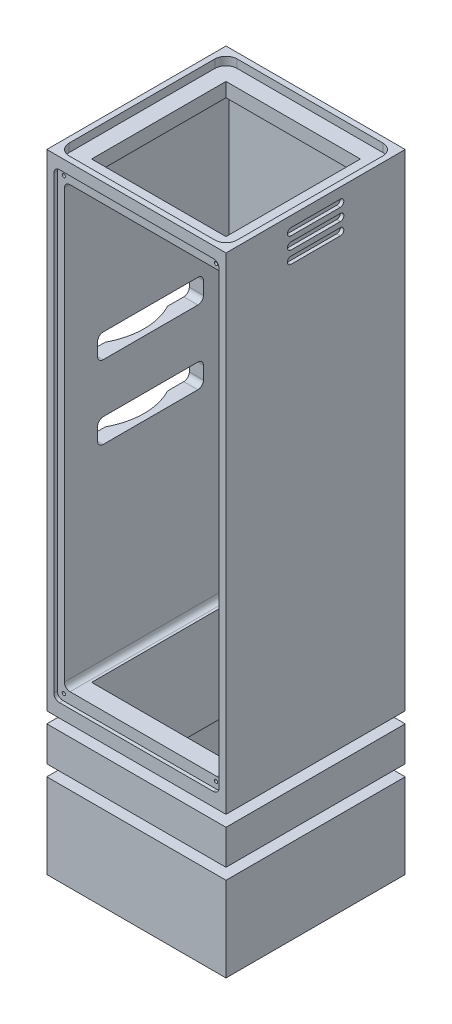
SolidWorks part; units mm, degrees
ref_plane "Front Plane" through (0, 0, 0) normal (0, 0, 1) x (1, 0, 0)
ref_plane "Top Plane" through (0, 0, 0) normal (0, 1, 0) x (1, 0, 0)
ref_plane "Right Plane" through (0, 0, 0) normal (1, 0, 0) x (0, 0, -1)
sketch "Sketch1" plane through (0, 0, 0) normal (0, 1, 0) x (1, 0, 0)
  line L0 (6.35, 44.45) -> (44.45, 44.45)
  line L1 (0, 0) -> (50.8, 0)
  line L2 (0, 0) -> (0, 50.8)
  line L3 (0, 50.8) -> (50.8, 50.8)
  line L4 (50.8, 0) -> (50.8, 50.8)
  line L5 (44.45, 6.35) -> (44.45, 44.45)
  line L6 (6.35, 6.35) -> (44.45, 6.35)
  line L7 (6.35, 6.35) -> (6.35, 44.45)
  dimension "D1" = 50.8
  dimension "D2" = 6.35
extrude "Boss-Extrude1" add sketch "Sketch1" along normal blind 178
sketch "Sketch2" plane through (0, 0, 0) normal (0, -1, 0) x (1, 0, 0)
  line L0 (47.8, -3) -> (3, -3)
  line L1 (3, -3) -> (3, -47.8)
  line L2 (3, -47.8) -> (47.8, -47.8)
  line L3 (47.8, -47.8) -> (47.8, -3)
  line L4 (6.35, -44.45) -> (44.45, -44.45)
  line L5 (6.35, -6.35) -> (6.35, -44.45)
  line L6 (44.45, -6.35) -> (6.35, -6.35)
  line L7 (44.45, -44.45) -> (44.45, -6.35)
  line L8 (6.35, -44.45) -> (44.45, -44.45)
  line L9 (6.35, -6.35) -> (6.35, -44.45)
  line L10 (44.45, -6.35) -> (6.35, -6.35)
  line L11 (44.45, -44.45) -> (44.45, -6.35)
  line L12 (0, -50.8) -> (0, 0) construction
  dimension "D2" = 3
  dimension "D1" = 0
extrude "Cut-Extrude1" cut sketch "Sketch2" against normal blind 20
sketch "Sketch3" plane through (0, 0, 0) normal (0, 0, 1) x (1, 0, 0)
  line L0 (0, 0) -> (50.8, 0) construction
  line L1 (2, 171.65) -> (48.8, 171.65)
  line L2 (2, 171.65) -> (2, 47.175)
  line L3 (2, 47.175) -> (48.8, 47.175)
  line L4 (48.8, 171.65) -> (48.8, 47.175)
  line L5 (0, 178) -> (0, 0) construction
  line L6 (50.8, 178) -> (50.8, 0) construction
  line L7 (0, 178) -> (50.8, 178) construction
  dimension "D1" = 47.175
  dimension "D2" = 2
  dimension "D3" = 2
  dimension "D4" = 6.35
extrude "Cut-Extrude2" cut sketch "Sketch3" against normal blind 47.625
sketch "Sketch4" plane through (0, 0, 0) normal (0, 0, 1) x (1, 0, 0)
  line L0 (0, 178) -> (0, 0) construction
  line L1 (0, 27.175) -> (50.8, 27.175)
  line L2 (0, 27.175) -> (0, 24)
  line L3 (0, 24) -> (50.8, 24)
  line L4 (50.8, 27.175) -> (50.8, 24)
  line L5 (50.8, 178) -> (50.8, 0) construction
  line L6 (0, 0) -> (50.8, 0) construction
  line L8 (0, 37) -> (50.8, 37)
  line L9 (0, 37) -> (0, 40.175)
  line L10 (0, 40.175) -> (50.8, 40.175)
  line L11 (50.8, 37) -> (50.8, 40.175)
  dimension "D1" = 24
  dimension "D2" = 3.175
  dimension "D3" = 13
extrude "Cut-Extrude3" cut sketch "Sketch4" against normal blind 3.175
sketch "Sketch5" plane through (0, 0, 0) normal (0, 0, 1) x (1, 0, 0)
  line L0 (50.8, 40.175) -> (0, 40.175) construction
  line L1 (0, 37) -> (3.175, 37)
  line L2 (0, 37) -> (0, 40.175)
  line L3 (0, 40.175) -> (3.175, 40.175)
  line L4 (3.175, 37) -> (3.175, 40.175)
  line L5 (0, 24) -> (50.8, 24) construction
  line L6 (0, 27.175) -> (3.175, 27.175)
  line L7 (0, 27.175) -> (0, 24)
  line L8 (0, 24) -> (3.175, 24)
  line L9 (3.175, 27.175) -> (3.175, 24)
  dimension "D1" = 3.175
extrude "Cut-Extrude4" cut sketch "Sketch5" against normal through all
ref_plane "Plane1" through (0, 0, -25.4) normal (0, 0, 1) x (1, 0, 0)
ref_plane "Plane2" through (25.4, 0, 0) normal (-1, 0, 0) x (0, 0, 1)
sketch "Sketch6" plane through (0, 0, 0) normal (-1, 0, 0) x (0, 0, 1)
  line L0 (-32.4, 174) -> (-18.4, 174) construction
  line L1 (-32.4, 175) -> (-18.4, 175)
  line L2 (-32.4, 173) -> (-18.4, 173)
  line L3 (-32.4, 170.5) -> (-18.4, 170.5) construction
  line L4 (-32.4, 171.5) -> (-18.4, 171.5)
  line L5 (-32.4, 169.5) -> (-18.4, 169.5)
  line L6 (-32.4, 167) -> (-18.4, 167) construction
  line L9 (-32.4, 168) -> (-18.4, 168)
  line L10 (-32.4, 166) -> (-18.4, 166)
  line L11 (-25.4, 174) -> (-25.4, 170.5) construction
  line L12 (-25.4, 170.5) -> (-25.4, 167) construction
  line L13 (-25.4, 174) -> (-25.4, 178) construction
  line L14 (-50.8, 178) -> (0, 178) construction
  arc A0 (-32.4, 175) -> (-32.4, 173) centre (-32.4, 174) ccw
  arc A1 (-18.4, 173) -> (-18.4, 175) centre (-18.4, 174) ccw
  arc A2 (-32.4, 171.5) -> (-32.4, 169.5) centre (-32.4, 170.5) ccw
  arc A3 (-18.4, 169.5) -> (-18.4, 171.5) centre (-18.4, 170.5) ccw
  arc A6 (-32.4, 168) -> (-32.4, 166) centre (-32.4, 167) ccw
  arc A7 (-18.4, 166) -> (-18.4, 168) centre (-18.4, 167) ccw
  point P2 (-25.4, 174)
  point P9 (-25.4, 170.5)
  point P16 (-25.4, 167)
  point P25 (-33.4, 167)
  point P26 (-17.4, 167)
  dimension "D1" = 3.5
  dimension "D2" = 2
  dimension "D3" = 4
  dimension "D4" = 16
extrude "Cut-Extrude5" cut sketch "Sketch6" against normal blind 1
mirror "Mirror1" about plane through (0, 0, -25.4) normal (0, 0, 1) of "Cut-Extrude3"
mirror "Mirror2" about plane through (25.4, 0, 0) normal (-1, 0, 0) of "Cut-Extrude5", "Cut-Extrude4"
sketch "Sketch7" plane through (0, 0, 0) normal (0, 0, 1) x (1, 0, 0)
  line L0 (0, 178) -> (50.8, 178) construction
  line L1 (2, 171.65) -> (48.8, 171.65)
  line L2 (2, 171.65) -> (2, 174.825)
  line L3 (2, 174.825) -> (48.8, 174.825)
  line L4 (48.8, 171.65) -> (48.8, 174.825)
  line L6 (2, 47.175) -> (48.8, 47.175)
  line L7 (2, 47.175) -> (2, 44)
  line L8 (2, 44) -> (48.8, 44)
  line L9 (48.8, 47.175) -> (48.8, 44)
  dimension "D1" = 3.175
extrude "Cut-Extrude6" cut sketch "Sketch7" against normal blind 1
fillet "Fillet1" radius 1.5875 12 edges at (47.8, 10, -47.8) (47.8, 10, -3) (3, 10, -47.8) (3, 10, -3) (48.8, 47.175, -24.3125) (2, 47.175, -24.3125) (48.8, 171.65, -24.3125) (2, 171.65, -24.3125) (48.8, 174.825, -0.5) (2, 174.825, -0.5) (48.8, 44, -0.5) (2, 44, -0.5)
sketch "Sketch8" plane through (0, 178, 0) normal (0, 1, 0) x (1, 0, 0)
  line L0 (0, 50.8) -> (0, 0) construction
  line L1 (4.7625, 49.2125) -> (46.0375, 49.2125)
  line L2 (1.5875, 46.0375) -> (1.5875, 4.7625)
  line L3 (4.7625, 1.5875) -> (46.0375, 1.5875)
  line L4 (49.2125, 46.0375) -> (49.2125, 4.7625)
  line L5 (50.8, 50.8) -> (0, 50.8) construction
  line L6 (0, 0) -> (50.8, 0) construction
  arc A0 (46.0375, 49.2125) -> (49.2125, 46.0375) centre (46.0375, 46.0375) cw
  arc A1 (49.2125, 4.7625) -> (46.0375, 1.5875) centre (46.0375, 4.7625) cw
  arc A2 (4.7625, 1.5875) -> (1.5875, 4.7625) centre (4.7625, 4.7625) cw
  arc A3 (1.5875, 46.0375) -> (4.7625, 49.2125) centre (4.7625, 46.0375) cw
  dimension "D1" = 3.175
  dimension "D2" = 1.5875
  dimension "D3" = 1.5875
  dimension "D4" = 1.5875
extrude "Cut-Extrude7" cut sketch "Sketch8" against normal blind 2.3444
hole_wizard "M1.2x0.25 Tapped Hole1" positions "Sketch12" profile "Sketch14" tap size "M1.2x0.25" standard "ANSI Metric"
sketch "Sketch12" plane through (0, 0, -1) normal (0, 0, 1) x (1, 0, 0)
  line L0 (2, 48.7625) -> (2, 45.5875) construction
  line L1 (3.5875, 44) -> (47.2125, 44) construction
  line L2 (3.8415, 172.9838) -> (3.8415, 45.8415) construction
  line L3 (3.8415, 45.8415) -> (46.9588, 45.8415) construction
  line L4 (46.9588, 45.8415) -> (46.9588, 172.9838) construction
  line L5 (46.9588, 172.9838) -> (3.8415, 172.9838) construction
  line L6 (47.2125, 174.825) -> (3.5875, 174.825) construction
  line L7 (48.8, 45.5875) -> (48.8, 173.2375) construction
  point P0 (3.8415, 172.9838)
  point P3 (46.9588, 172.9838)
  point P6 (3.8415, 45.8415)
  point P9 (46.9588, 45.8415)
  dimension "D1" = 1.8415
  dimension "D2" = 1.8415
  dimension "D3" = 1.8412
  dimension "D4" = 1.8412
sketch "Sketch14" plane through (3.8415, 172.9838, -1) normal (1, 0, 0) x (0, -1, 0)
  line L0 (0, 0) -> (0, 3.2851)
  line L1 (0, 3.2851) -> (0.475, 2.9997)
  line L2 (0.475, 2.9997) -> (0.475, 0)
  line L5 (0.475, 0) -> (0, 0)
  line L10 (0, 3.2851) -> (-0.475, 2.9997) construction
  line L11 (0, -6.35) -> (0, 107.95) construction
  dimension "Tap Drill Dia." = 0.95
  dimension "Tap Drill Depth" = 2.9997
  dimension "Drill Angle" = 118
cosmetic thread "Hole Thread5" parameters "D1"=2.4, "D2"=1.2
cosmetic thread "Hole Thread6" parameters "D1"=2.4, "D2"=1.2
cosmetic thread "Hole Thread7" parameters "D1"=2.4, "D2"=1.2
cosmetic thread "Hole Thread8" parameters "D1"=2.4, "D2"=1.2
sketch "Sketch17" plane through (0, 0, -1) normal (0, 0, 1) x (1, 0, 0)
  line L0 (2, 170.0625) -> (2, 48.7625) construction
  line L1 (2, 170.0625) -> (2, 48.7625)
  line L2 (4, 170.0625) -> (4, 48.7625)
  line L3 (3.5875, 47.175) -> (47.2125, 47.175) construction
  line L4 (47.2125, 47.175) -> (3.5875, 47.175) construction
  line L5 (47.2125, 171.65) -> (3.5875, 171.65) construction
  line L6 (3.5875, 171.65) -> (47.2125, 171.65) construction
  line L7 (3.5875, 171.65) -> (5.5875, 171.65)
  line L8 (3.5875, 47.175) -> (5.5875, 47.175)
  arc A0 (2, 48.7625) -> (3.5875, 47.175) centre (3.5875, 48.7625) ccw construction
  arc A1 (3.5875, 171.65) -> (2, 170.0625) centre (3.5875, 170.0625) ccw construction
  arc A2 (2, 48.7625) -> (3.5875, 47.175) centre (3.5875, 48.7625) ccw
  arc A3 (3.5875, 171.65) -> (2, 170.0625) centre (3.5875, 170.0625) ccw
  arc A4 (4, 48.7625) -> (5.5875, 47.175) centre (5.5875, 48.7625) ccw
  arc A5 (5.5875, 171.65) -> (4, 170.0625) centre (5.5875, 170.0625) ccw
  dimension "D1" = 2
extrude "Boss-Extrude2" add sketch "Sketch17" against normal up to next
sketch "Sketch15" plane through (0, 0, 0) normal (-1, 0, 0) x (0, 0, 1)
  line L0 (-50.8, 0) -> (0, 0) construction
  line L3 (-25.4, 101.6) -> (-25.4, 40.175) construction
  line L7 (-47.625, 40.175) -> (-3.175, 40.175) construction
  line L11 (-40.4, 108.4) -> (-10.4, 108.4)
  line L12 (-40.4, 108.4) -> (-40.4, 101.6)
  line L13 (-40.4, 101.6) -> (-10.4, 101.6)
  line L14 (-10.4, 108.4) -> (-10.4, 101.6)
  line L15 (-40.4, 129.2) -> (-10.4, 129.2)
  line L16 (-40.4, 129.2) -> (-40.4, 122.4)
  line L17 (-40.4, 122.4) -> (-10.4, 122.4)
  line L18 (-10.4, 129.2) -> (-10.4, 122.4)
  dimension "D1" = 101.6
  dimension "D5" = 30
  dimension "D6" = 6.8
  dimension "D7" = 14
extrude "Cut-Extrude8" cut sketch "Sketch15" against normal up to next
fillet "Fillet2" radius 1.5875 8 edges at (2, 101.6, -10.4) (2, 101.6, -40.4) (2, 108.4, -40.4) (2, 108.4, -10.4) (2, 122.4, -10.4) (2, 129.2, -10.4) (2, 122.4, -40.4) (2, 129.2, -40.4)
ref_plane "Plane4" through (0, 125.8, 0) normal (0, 1, 0) x (1, 0, 0)
sketch "Sketch20" plane through (0, 125.8, 0) normal (0, 1, 0) x (1, 0, 0)
  line L0 (-16.55, 25.4) -> (2.5, 25.4)
  line L1 (0, 38.8125) -> (0, 11.9875) construction
  line L2 (-16.55, 25.4) -> (-35.6, 25.4)
  arc A0 (-35.6, 25.4) -> (2.5, 25.4) centre (-16.55, 25.4) ccw
  point P1 (0, 25.4)
  point P3 (2.5, 25.4)
  dimension "D2" = 38.1
  dimension "D1" = 2.5
revolve "Cut-Revolve1" cut sketch "Sketch20" angle 360 about L0
pattern_linear "LPattern1" count 2 spacing 20.8 along (0, -1, 0) of "Cut-Revolve1"
